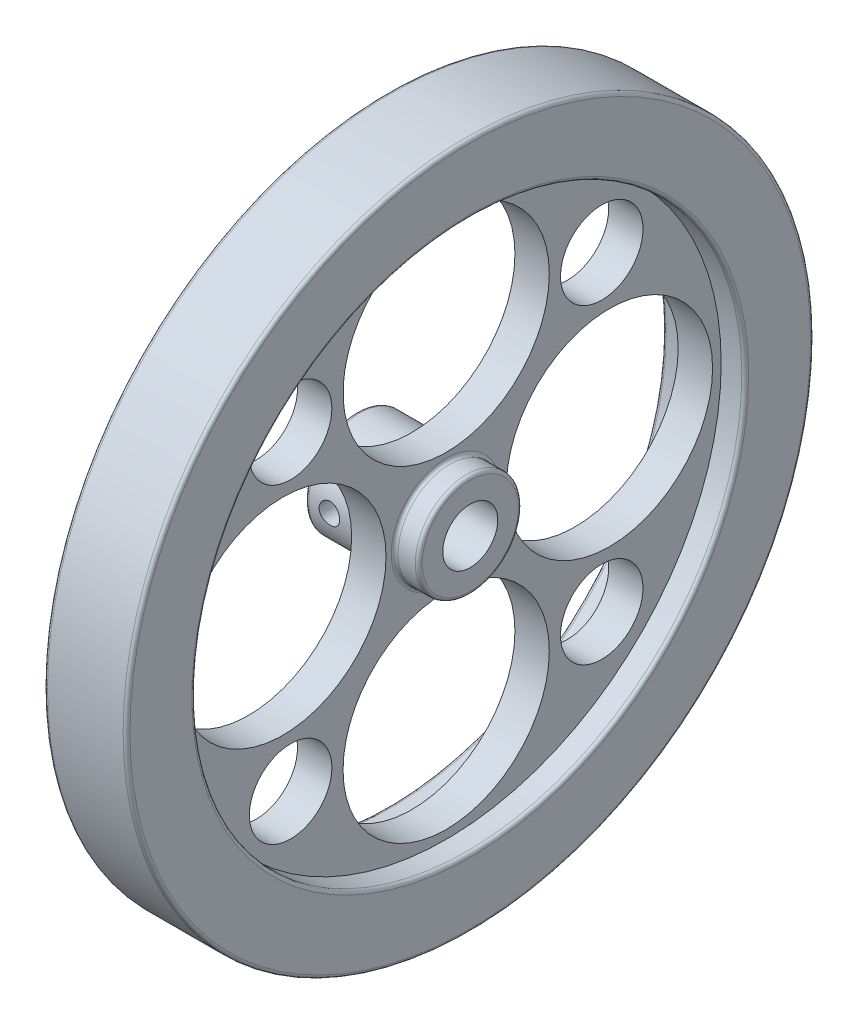
SolidWorks part; units mm, degrees
ref_plane "Front Plane" through (0, 0, 0) normal (0, 0, 1) x (1, 0, 0)
ref_plane "Top Plane" through (0, 0, 0) normal (0, 1, 0) x (1, 0, 0)
ref_plane "Right Plane" through (0, 0, 0) normal (1, 0, 0) x (0, 0, -1)
sketch "Sketch1" plane through (0, 0, 0) normal (1, 0, 0) x (0, 0, -1)
  circle A0 centre (0, 0) radius 7.5
  circle A1 centre (0, 0) radius 4
  dimension "D1" = 15
  dimension "D2" = 8
extrude "Boss-Extrude1" add sketch "Sketch1" along normal blind 16.5
sketch "Sketch2" plane through (16.5, 0, 0) normal (1, 0, 0) x (0, 0, -1)
  circle A0 centre (0, 0) radius 40
  circle A1 centre (0, 0) radius 7.5 construction
  circle A2 centre (0, 0) radius 7.5
  dimension "D1" = 80
extrude "Boss-Extrude2" add sketch "Sketch2" against normal blind 5 from offset 3.5 offset against normal yes
sketch "Sketch3" plane through (16.5, 0, 0) normal (1, 0, 0) x (0, 0, -1)
  circle A0 centre (0, 0) radius 50
  circle A1 centre (0, 0) radius 40 construction
  circle A2 centre (0, 0) radius 40
  dimension "D1" = 100
extrude "Boss-Extrude3" add sketch "Sketch3" against normal blind 12
sketch "Sketch4" plane through (13, 0, 0) normal (1, 0, 0) x (0, 0, -1)
  line L0 (0, 0) -> (0, 50.8287) construction
  line L1 (0, 0) -> (-22.6274, 22.6274) construction
  circle A0 centre (0, 0) radius 23.75 construction
  circle A1 centre (0, 0) radius 32 construction
  circle A2 centre (0, 23.75) radius 15
  circle A3 centre (-22.6274, 22.6274) radius 6
  dimension "D1" = 47.5
  dimension "D2" = 64
  dimension "D4" = 12
  dimension "D5" = 30
  dimension "D3" = 45
extrude "Cut-Extrude1" cut sketch "Sketch4" against normal up to next
pattern_circular "CirPattern1" count 4 over 360 about axis through (0, 0, 0) along (1, 0, 0) of "Cut-Extrude1"
sketch "Sketch5" plane through (0, 0, 0) normal (0, 0, 1) x (1, 0, 0)
  line L0 (0, 7.5) -> (0, -7.5) construction
  circle A0 centre (3.5, 0) radius 1.5
  dimension "D1" = 3
  dimension "D2" = 3.5
extrude "Cut-Extrude2" cut sketch "Sketch5" against normal mid plane 42
fillet "Fillet1" radius 0.5 8 edges at (4.5, 0, -40) (4.5, 0, -50) (8, 0, -7.5) (0, 0, -7.5) (13, 0, -7.5) (16.5, 0, -50) (16.5, 0, -40) (16.5, 0, -7.5)
